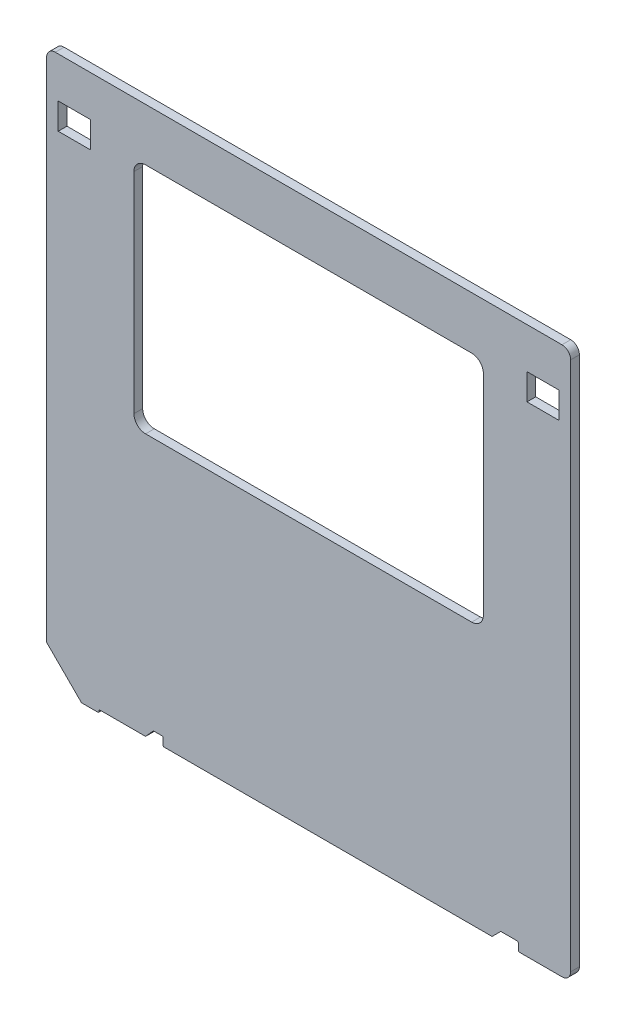
SolidWorks part; units mm, degrees
ref_plane "Plane1" through (0, 0, 0) normal (0, 0, 1) x (1, 0, 0)
ref_plane "Plane2" through (0, 0, 0) normal (0, 1, 0) x (1, 0, 0)
ref_plane "Plane3" through (0, 0, 0) normal (1, 0, 0) x (0, 0, -1)
sketch "Sketch1" plane through (0, 0, 0) normal (0, 0, 1) x (1, 0, 0)
  line L0 (-43.5, 47) -> (0, 47)
  line L1 (-45, 45.5) -> (-45, -41.5)
  line L2 (-25, -45.7) -> (-25, -46.8)
  line L3 (45, -45.5) -> (45, 45.5)
  line L4 (0, 47) -> (0, -47) construction
  line L5 (-45, -41.5) -> (-39, -47.5)
  line L6 (-36, -47.3) -> (-36, -47.2)
  line L7 (-35.8, -47) -> (-28, -47)
  line L8 (-28, -47) -> (-26.6618, -45.5)
  line L9 (-26.6618, -45.5) -> (-25.2, -45.5)
  line L11 (-36.2, -47.5) -> (-39, -47.5)
  line L13 (0, 47) -> (43.5, 47)
  line L14 (36, -45.7) -> (36, -46.8)
  line L16 (31.5, -47) -> (32.9414, -45.5586)
  line L17 (33.0828, -45.5) -> (35.8, -45.5)
  line L18 (36.2, -47) -> (43.5, -47)
  line L23 (-24.8, -47) -> (31.5, -47)
  arc A0 (-45, 45.5) -> (-43.5, 47) centre (-43.5, 45.5) cw
  arc A1 (45, 45.5) -> (43.5, 47) centre (43.5, 45.5) ccw
  arc A2 (45, -45.5) -> (43.5, -47) centre (43.5, -45.5) cw
  arc A3 (-36, -47.3) -> (-36.2, -47.5) centre (-36.2, -47.3) cw
  arc A4 (-36, -47.2) -> (-35.8, -47) centre (-35.8, -47.2) cw
  arc A5 (-24.8, -47) -> (-25, -46.8) centre (-24.8, -46.8) cw
  arc A6 (-25.2, -45.5) -> (-25, -45.7) centre (-25.2, -45.7) cw
  arc A7 (36.2, -47) -> (36, -46.8) centre (36.2, -46.8) cw
  arc A8 (36, -45.7) -> (35.8, -45.5) centre (35.8, -45.7) ccw
  arc A9 (32.9414, -45.5586) -> (33.0828, -45.5) centre (33.0828, -45.7) cw
  point P21 (-45, 47)
  point P25 (45, 47)
  point P30 (-36, -47.5)
  point P37 (-36, -47)
  point P46 (36, -47)
  point P49 (36, -45.5)
  point P52 (33, -45.5)
  dimension "D14" = 1.5
  dimension "D6" = 0.2
  dimension "D8" = 0.2
  dimension "D4" = 0.2
  dimension "D1" = 90
  dimension "D2" = 6
  dimension "D3" = 0.5
  dimension "D5" = 3
  dimension "D11" = 9
  dimension "D12" = 1.5
  dimension "D13" = 3
extrude "Base-Extrude" add sketch "Sketch1" along normal blind 1.5
sketch "Sketch13" plane through (0, 0, 0) normal (0, 0, 1) x (1, 0, 0)
  line L0 (-43.5, 47) -> (43.5, 47) construction
  line L1 (-28, 38) -> (28, 38)
  line L2 (-30, 36) -> (-30, 0)
  line L3 (-28, -2) -> (28, -2)
  line L4 (30, 36) -> (30, 0)
  line L5 (0, 49.9964) -> (0, -12.4363) construction
  arc A0 (-30, 0) -> (-28, -2) centre (-28, 0) ccw
  arc A1 (28, -2) -> (30, 0) centre (28, 0) ccw
  arc A2 (28, 38) -> (30, 36) centre (28, 36) cw
  arc A3 (-28, 38) -> (-30, 36) centre (-28, 36) ccw
  point P5 (0, 38)
  point P12 (-30, -2)
  point P17 (30, 38)
  point P20 (-30, 38)
  dimension "D4" = 2
  dimension "D1" = 60
  dimension "D2" = 40
  dimension "D3" = 9
sketch "Sketch2" plane through (0, 0, 1.5) normal (0, 0, 1) x (1, 0, 0)
  line L0 (36, 47) -> (36, -5.5)
  line L1 (-25, -45.5) -> (-25, -47)
  line L2 (36, 47) -> (-36, 47)
  line L3 (0, 50.9738) -> (0, -3.8279) construction
  line L4 (33.5, -8) -> (-33.5, -8)
  line L5 (-36, 47) -> (-36, -5.5)
  line L6 (-25, -17.5) -> (-25, -45.5)
  line L7 (-45, 45.5) -> (-45, -41.5) construction
  line L8 (-22.5, -15) -> (33.5, -15)
  line L10 (-43.5, 47) -> (43.5, 47) construction
  line L11 (36, -17.5) -> (36, -47)
  line L21 (-24.8, -47) -> (31.5, -47) construction
  line L24 (-25, -47) -> (36, -47)
  arc A0 (33.5, -8) -> (36, -5.5) centre (33.5, -5.5) ccw
  arc A1 (-33.5, -8) -> (-36, -5.5) centre (-33.5, -5.5) cw
  arc A2 (-22.5, -15) -> (-25, -17.5) centre (-22.5, -17.5) ccw
  arc A3 (36, -17.5) -> (33.5, -15) centre (33.5, -17.5) ccw
  point P8 (0, 47)
  point P11 (36, -8)
  point P15 (0, -8)
  point P28 (-25, -15)
  point P31 (36, -15)
  dimension "D2" = 2.5
  dimension "D4" = 2.5
  dimension "D1" = 55
  dimension "D3" = 20
  dimension "D5" = 9
  dimension "D6" = 7
extrude "Cut-Extrude1" [suppressed] cut sketch "Sketch2" against normal blind 0.25
sketch "Sketch5" [suppressed] plane through (0, 0, 1.25) normal (0, 0, 1) x (1, 0, 0)
  line L0 (-22.4, -15.2) -> (20.3, -15.2)
  line L1 (-24.8, -17.6) -> (-24.8, -46.95)
  line L2 (22.7, -46.95) -> (-24.8, -46.95)
  line L3 (22.7, -46.95) -> (22.7, -17.6)
  line L4 (-22.5, -15) -> (33.5, -15) construction
  line L5 (-25, -17.5) -> (-25, -45.7) construction
  line L6 (-16.8, -17.2) -> (-5.8, -17.2)
  line L7 (-17.3, -17.7) -> (-17.3, -41.2)
  line L9 (-5.8, -41.7) -> (-16.8, -41.7)
  line L10 (-5.3, -41.2) -> (-5.3, -17.7)
  arc A0 (-24.8, -17.6) -> (-22.4, -15.2) centre (-22.4, -17.6) cw
  arc A1 (22.7, -17.6) -> (20.3, -15.2) centre (20.3, -17.6) ccw
  arc A2 (-17.3, -17.7) -> (-16.8, -17.2) centre (-16.8, -17.7) cw
  arc A3 (-5.3, -17.7) -> (-5.8, -17.2) centre (-5.8, -17.7) ccw
  arc A4 (-5.3, -41.2) -> (-5.8, -41.7) centre (-5.8, -41.2) cw
  arc A5 (-16.8, -41.7) -> (-17.3, -41.2) centre (-16.8, -41.2) cw
  point P10 (-24.8, -15.2)
  point P13 (22.7, -15.2)
  point P21 (-17.3, -17.2)
  point P24 (-5.3, -17.2)
  point P27 (-5.3, -41.7)
  dimension "D1" = 31.75
  dimension "D3" = 0.2
  dimension "D5" = 2.4
  dimension "D10" = 0.5
  dimension "D2" = 47.5
  dimension "D4" = 0.2
  dimension "D6" = 12
  dimension "D7" = 24.5
  dimension "D8" = 2
  dimension "D9" = 7.5
extrude "Boss-Extrude2" [suppressed] add sketch "Sketch5" along normal blind 0.25
sketch "Sketch8" [suppressed] plane through (0, 0, 0) normal (0, 0, -1) x (-1, 0, 0)
  line L1 (22.5, -15) -> (-33.5, -15) construction
  circle A0 centre (0, 0.8) radius 13.25
  dimension "D1" = 26.5
  dimension "D2" = 15.8
sketch "Sketch12" plane through (0, 0, 1.5) normal (0, 0, 1) x (1, 0, 0)
  line L0 (37.4999, 40) -> (42.9999, 40)
  line L1 (37.4999, 40) -> (37.4999, 35.5)
  line L2 (42.9999, 35.5) -> (37.4999, 35.5)
  line L3 (42.9999, 35.5) -> (42.9999, 40)
  line L4 (-43.5, 47) -> (43.5, 47) construction
  line L5 (45, -45.5) -> (45, 45.5) construction
  line L6 (0, 44.1837) -> (0, 40) construction
  line L7 (-42.9999, 35.5) -> (-42.9999, 40)
  line L8 (-42.9999, 35.5) -> (-37.4999, 35.5)
  line L9 (-37.4999, 40) -> (-37.4999, 35.5)
  line L10 (-37.4999, 40) -> (-42.9999, 40)
  dimension "D1" = 5.5
  dimension "D2" = 4.5
  dimension "D3" = 7
  dimension "D4" = 2.0001
extrude "Cut-Extrude5" cut sketch "Sketch12" against normal through all
extrude "Cut-Extrude7" cut sketch "Sketch13" along normal through all
